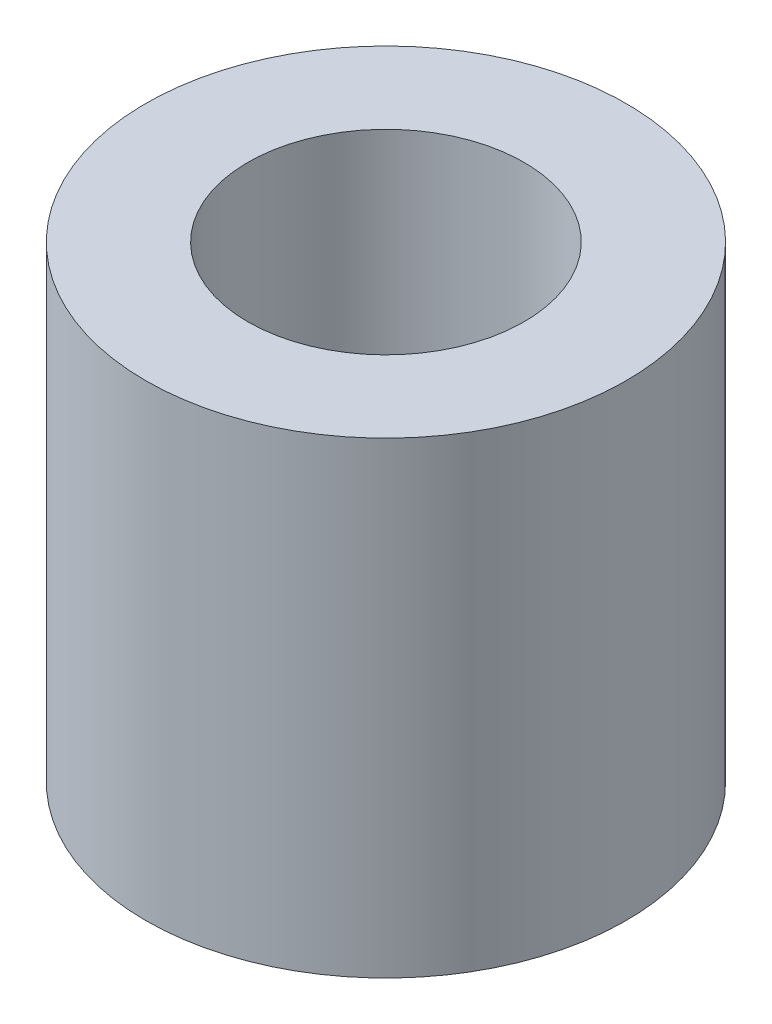
SolidWorks part; units mm, degrees
ref_plane "Front Plane" through (0, 0, 0) normal (0, 0, 1) x (1, 0, 0)
ref_plane "Top Plane" through (0, 0, 0) normal (0, 1, 0) x (1, 0, 0)
ref_plane "Right Plane" through (0, 0, 0) normal (1, 0, 0) x (0, 0, -1)
sketch "Sketch1" plane through (0, 0, 0) normal (0, 1, 0) x (1, 0, 0)
  circle A0 centre (0, 0) radius 5.65
  circle A1 centre (0, 0) radius 3.25
  dimension "D1" = 6.5
  dimension "D2" = 2.4
extrude "Boss-Extrude1" add sketch "Sketch1" along normal blind 11
